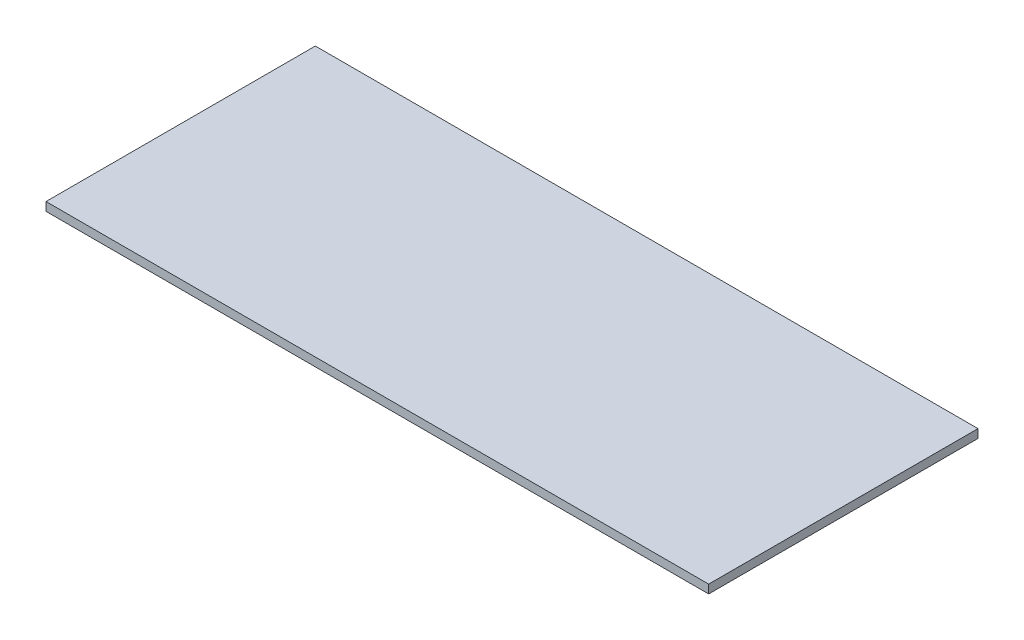
SolidWorks part; units mm, degrees
ref_plane "Front Plane" through (0, 0, 0) normal (0, 0, 1) x (1, 0, 0)
ref_plane "Top Plane" through (0, 0, 0) normal (0, 1, 0) x (1, 0, 0)
ref_plane "Right Plane" through (0, 0, 0) normal (1, 0, 0) x (0, 0, -1)
sketch "Sketch1" plane through (0, 0, 0) normal (0, 1, 0) x (1, 0, 0)
  line L1 (-196.85, 80.01) -> (196.85, 80.01)
  line L2 (-196.85, 80.01) -> (-196.85, -80.01)
  line L3 (-196.85, -80.01) -> (196.85, -80.01)
  line L4 (196.85, 80.01) -> (196.85, -80.01)
  line L5 (-196.85, 80.01) -> (196.85, -80.01) construction
  line L6 (-196.85, -80.01) -> (196.85, 80.01) construction
  point P0 (0, 0)
  dimension "D1" = 393.7
  dimension "D2" = 160.02
extrude "Boss-Extrude1" add sketch "Sketch1" along normal blind 5.08
